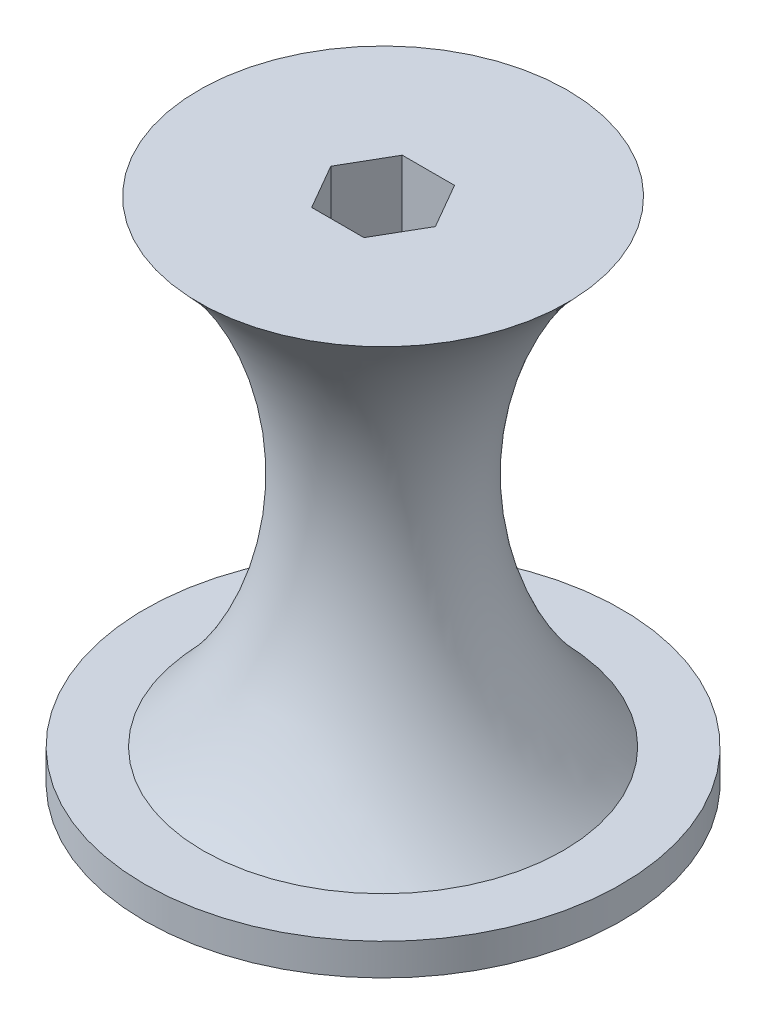
SolidWorks part; units mm, degrees
ref_plane "Front Plane" through (0, 0, 0) normal (0, 0, 1) x (1, 0, 0)
ref_plane "Top Plane" through (0, 0, 0) normal (0, 1, 0) x (1, 0, 0)
ref_plane "Right Plane" through (0, 0, 0) normal (1, 0, 0) x (0, 0, -1)
sketch "Sketch1" plane through (0, 0, 0) normal (0, 1, 0) x (1, 0, 0)
  circle A0 centre (0, 0) radius 38.1
  dimension "D1" = 76.2
extrude "Boss-Extrude1" add sketch "Sketch1" against normal blind 5.08
sketch "Sketch4" plane through (0, 0, 0) normal (0, 0, 1) x (1, 0, 0)
  line L0 (0, 0) -> (0, 76.1958)
  line L1 (0, 76.1958) -> (29.4498, 76.1958)
  line L3 (28.7869, 0) -> (0, 0)
  arc A1 (29.4498, 76.1958) -> (28.7869, 0) centre (66.9204, 37.7691) ccw
revolve "Revolve1" add sketch "Sketch4" angle 360 about L0
sketch "Sketch5" plane through (0, -5.08, 0) normal (0, -1, 0) x (-1, 0, 0)
  line L1 (8.3589, 0) -> (4.1794, 7.239)
  line L2 (4.1794, 7.239) -> (-4.1794, 7.239)
  line L3 (-4.1794, 7.239) -> (-8.3589, 0)
  line L4 (-8.3589, 0) -> (-4.1794, -7.239)
  line L5 (-4.1794, -7.239) -> (4.1794, -7.239)
  line L6 (4.1794, -7.239) -> (8.3589, 0)
  circle A0 centre (0, 0) radius 7.239 construction
  dimension "D1" = 14.478
extrude "Cut-Extrude1" cut sketch "Sketch5" against normal through all
